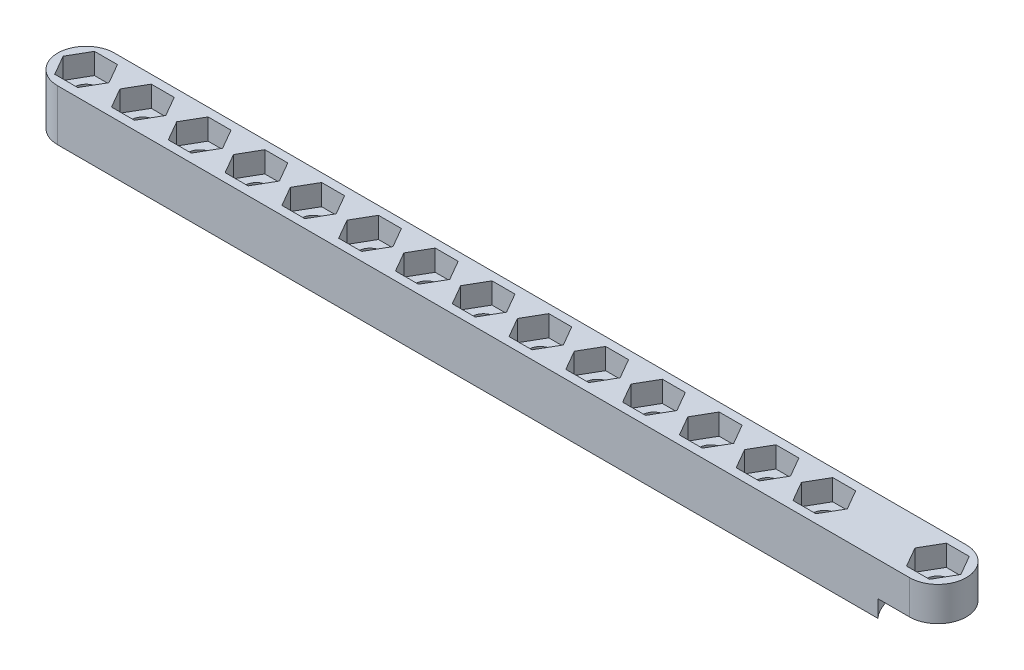
SolidWorks part; units mm, degrees
ref_plane "Front Plane" through (0, 0, 0) normal (0, 0, 1) x (1, 0, 0)
ref_plane "Top Plane" through (0, 0, 0) normal (0, 1, 0) x (1, 0, 0)
ref_plane "Right Plane" through (0, 0, 0) normal (1, 0, 0) x (0, 0, -1)
sketch "Sketch1" plane through (0, 0, 0) normal (0, 1, 0) x (1, 0, 0)
  line L0 (0, 0) -> (-150, 0) construction
  line L1 (0, -5) -> (-150, -5)
  line L2 (0, 5) -> (-150, 5)
  arc A0 (0, -5) -> (0, 5) centre (0, 0) ccw
  arc A1 (-150, 5) -> (-150, -5) centre (-150, 0) ccw
  circle A2 centre (0, 0) radius 2.05
  circle A7 centre (-50, 0) radius 2.05
  circle A8 centre (-60, 0) radius 2.05
  circle A9 centre (-70, 0) radius 2.05
  circle A10 centre (-80, 0) radius 2.05
  circle A11 centre (-90, 0) radius 2.05
  circle A12 centre (-100, 0) radius 2.05
  circle A13 centre (-110, 0) radius 2.05
  circle A14 centre (-120, 0) radius 2.05
  circle A15 centre (-130, 0) radius 2.05
  circle A16 centre (-140, 0) radius 2.05
  circle A17 centre (-150, 0) radius 2.05
  circle A18 centre (-10, 0) radius 2.05 [skipped]
  circle A19 centre (-20, 0) radius 2.05
  circle A20 centre (-30, 0) radius 2.05
  circle A21 centre (-40, 0) radius 2.05
  point P3 (-75, 0)
  dimension "D3" = 4.1
  dimension "D1" = 150
  dimension "D2" = 10
  dimension "D4" = 16
extrude "Boss-Extrude1" add sketch "Sketch1" along normal blind 6
sketch "Sketch2" plane through (0, 6, 0) normal (0, 1, 0) x (1, 0, 0)
  line L1 (4.0415, 0) -> (2.0207, 3.5)
  line L2 (2.0207, 3.5) -> (-2.0207, 3.5)
  line L3 (-2.0207, 3.5) -> (-4.0415, 0)
  line L4 (-4.0415, 0) -> (-2.0207, -3.5)
  line L5 (-2.0207, -3.5) -> (2.0207, -3.5)
  line L6 (2.0207, -3.5) -> (4.0415, 0)
  line L30 (-45.9585, 0) -> (-47.9793, 3.5)
  line L31 (-47.9793, 3.5) -> (-52.0207, 3.5)
  line L32 (-52.0207, 3.5) -> (-54.0415, 0)
  line L33 (-54.0415, 0) -> (-52.0207, -3.5)
  line L34 (-52.0207, -3.5) -> (-47.9793, -3.5)
  line L35 (-47.9793, -3.5) -> (-45.9585, 0)
  line L36 (-55.9585, 0) -> (-57.9793, 3.5)
  line L37 (-57.9793, 3.5) -> (-62.0207, 3.5)
  line L38 (-62.0207, 3.5) -> (-64.0415, 0)
  line L39 (-64.0415, 0) -> (-62.0207, -3.5)
  line L40 (-62.0207, -3.5) -> (-57.9793, -3.5)
  line L41 (-57.9793, -3.5) -> (-55.9585, 0)
  line L42 (-65.9585, 0) -> (-67.9793, 3.5)
  line L43 (-67.9793, 3.5) -> (-72.0207, 3.5)
  line L44 (-72.0207, 3.5) -> (-74.0415, 0)
  line L45 (-74.0415, 0) -> (-72.0207, -3.5)
  line L46 (-72.0207, -3.5) -> (-67.9793, -3.5)
  line L47 (-67.9793, -3.5) -> (-65.9585, 0)
  line L48 (-75.9585, 0) -> (-77.9793, 3.5)
  line L49 (-77.9793, 3.5) -> (-82.0207, 3.5)
  line L50 (-82.0207, 3.5) -> (-84.0415, 0)
  line L51 (-84.0415, 0) -> (-82.0207, -3.5)
  line L52 (-82.0207, -3.5) -> (-77.9793, -3.5)
  line L53 (-77.9793, -3.5) -> (-75.9585, 0)
  line L54 (-85.9585, 0) -> (-87.9793, 3.5)
  line L55 (-87.9793, 3.5) -> (-92.0207, 3.5)
  line L56 (-92.0207, 3.5) -> (-94.0415, 0)
  line L57 (-94.0415, 0) -> (-92.0207, -3.5)
  line L58 (-92.0207, -3.5) -> (-87.9793, -3.5)
  line L59 (-87.9793, -3.5) -> (-85.9585, 0)
  line L60 (-95.9585, 0) -> (-97.9793, 3.5)
  line L61 (-97.9793, 3.5) -> (-102.0207, 3.5)
  line L62 (-102.0207, 3.5) -> (-104.0415, 0)
  line L63 (-104.0415, 0) -> (-102.0207, -3.5)
  line L64 (-102.0207, -3.5) -> (-97.9793, -3.5)
  line L65 (-97.9793, -3.5) -> (-95.9585, 0)
  line L66 (-105.9585, 0) -> (-107.9793, 3.5)
  line L67 (-107.9793, 3.5) -> (-112.0207, 3.5)
  line L68 (-112.0207, 3.5) -> (-114.0415, 0)
  line L69 (-114.0415, 0) -> (-112.0207, -3.5)
  line L70 (-112.0207, -3.5) -> (-107.9793, -3.5)
  line L71 (-107.9793, -3.5) -> (-105.9585, 0)
  line L72 (-115.9585, 0) -> (-117.9793, 3.5)
  line L73 (-117.9793, 3.5) -> (-122.0207, 3.5)
  line L74 (-122.0207, 3.5) -> (-124.0415, 0)
  line L75 (-124.0415, 0) -> (-122.0207, -3.5)
  line L76 (-122.0207, -3.5) -> (-117.9793, -3.5)
  line L77 (-117.9793, -3.5) -> (-115.9585, 0)
  line L78 (-125.9585, 0) -> (-127.9793, 3.5)
  line L79 (-127.9793, 3.5) -> (-132.0207, 3.5)
  line L80 (-132.0207, 3.5) -> (-134.0415, 0)
  line L81 (-134.0415, 0) -> (-132.0207, -3.5)
  line L82 (-132.0207, -3.5) -> (-127.9793, -3.5)
  line L83 (-127.9793, -3.5) -> (-125.9585, 0)
  line L84 (-135.9585, 0) -> (-137.9793, 3.5)
  line L85 (-137.9793, 3.5) -> (-142.0207, 3.5)
  line L86 (-142.0207, 3.5) -> (-144.0415, 0)
  line L87 (-144.0415, 0) -> (-142.0207, -3.5)
  line L88 (-142.0207, -3.5) -> (-137.9793, -3.5)
  line L89 (-137.9793, -3.5) -> (-135.9585, 0)
  line L90 (-145.9585, 0) -> (-147.9793, 3.5)
  line L91 (-147.9793, 3.5) -> (-152.0207, 3.5)
  line L92 (-152.0207, 3.5) -> (-154.0415, 0)
  line L93 (-154.0415, 0) -> (-152.0207, -3.5)
  line L94 (-152.0207, -3.5) -> (-147.9793, -3.5)
  line L95 (-147.9793, -3.5) -> (-145.9585, 0)
  line L96 (-5.9585, 0) -> (-7.9793, 3.5) [skipped]
  line L97 (-7.9793, 3.5) -> (-12.0207, 3.5) [skipped]
  line L98 (-12.0207, 3.5) -> (-14.0415, 0) [skipped]
  line L99 (-14.0415, 0) -> (-12.0207, -3.5) [skipped]
  line L100 (-12.0207, -3.5) -> (-7.9793, -3.5) [skipped]
  line L101 (-7.9793, -3.5) -> (-5.9585, 0) [skipped]
  line L102 (-15.9585, 0) -> (-17.9793, 3.5) [skipped]
  line L103 (-17.9793, 3.5) -> (-22.0207, 3.5) [skipped]
  line L104 (-22.0207, 3.5) -> (-24.0415, 0) [skipped]
  line L105 (-24.0415, 0) -> (-22.0207, -3.5) [skipped]
  line L106 (-22.0207, -3.5) -> (-17.9793, -3.5) [skipped]
  line L107 (-17.9793, -3.5) -> (-15.9585, 0) [skipped]
  line L108 (-25.9585, 0) -> (-27.9793, 3.5) [skipped]
  line L109 (-27.9793, 3.5) -> (-32.0207, 3.5) [skipped]
  line L110 (-32.0207, 3.5) -> (-34.0415, 0) [skipped]
  line L111 (-34.0415, 0) -> (-32.0207, -3.5) [skipped]
  line L112 (-32.0207, -3.5) -> (-27.9793, -3.5) [skipped]
  line L113 (-27.9793, -3.5) -> (-25.9585, 0) [skipped]
  line L114 (-35.9585, 0) -> (-37.9793, 3.5) [skipped]
  line L115 (-37.9793, 3.5) -> (-42.0207, 3.5) [skipped]
  line L116 (-42.0207, 3.5) -> (-44.0415, 0) [skipped]
  line L117 (-44.0415, 0) -> (-42.0207, -3.5) [skipped]
  line L118 (-42.0207, -3.5) -> (-37.9793, -3.5) [skipped]
  line L119 (-37.9793, -3.5) -> (-35.9585, 0) [skipped]
  line L120 (-5.9585, 0) -> (-7.9793, 3.5) [skipped]
  line L121 (-7.9793, 3.5) -> (-12.0207, 3.5) [skipped]
  line L122 (-12.0207, 3.5) -> (-14.0415, 0) [skipped]
  line L123 (-14.0415, 0) -> (-12.0207, -3.5) [skipped]
  line L124 (-12.0207, -3.5) -> (-7.9793, -3.5) [skipped]
  line L125 (-7.9793, -3.5) -> (-5.9585, 0) [skipped]
  line L126 (-15.9585, 0) -> (-17.9793, 3.5)
  line L127 (-17.9793, 3.5) -> (-22.0207, 3.5)
  line L128 (-22.0207, 3.5) -> (-24.0415, 0)
  line L129 (-24.0415, 0) -> (-22.0207, -3.5)
  line L130 (-22.0207, -3.5) -> (-17.9793, -3.5)
  line L131 (-17.9793, -3.5) -> (-15.9585, 0)
  line L132 (-25.9585, 0) -> (-27.9793, 3.5)
  line L133 (-27.9793, 3.5) -> (-32.0207, 3.5)
  line L134 (-32.0207, 3.5) -> (-34.0415, 0)
  line L135 (-34.0415, 0) -> (-32.0207, -3.5)
  line L136 (-32.0207, -3.5) -> (-27.9793, -3.5)
  line L137 (-27.9793, -3.5) -> (-25.9585, 0)
  line L138 (-35.9585, 0) -> (-37.9793, 3.5)
  line L139 (-37.9793, 3.5) -> (-42.0207, 3.5)
  line L140 (-42.0207, 3.5) -> (-44.0415, 0)
  line L141 (-44.0415, 0) -> (-42.0207, -3.5)
  line L142 (-42.0207, -3.5) -> (-37.9793, -3.5)
  line L143 (-37.9793, -3.5) -> (-35.9585, 0)
  circle A0 centre (0, 0) radius 3.5 construction
  circle A5 centre (-50, 0) radius 3.5 construction
  circle A6 centre (-60, 0) radius 3.5 construction
  circle A7 centre (-70, 0) radius 3.5 construction
  circle A8 centre (-80, 0) radius 3.5 construction
  circle A9 centre (-90, 0) radius 3.5 construction
  circle A10 centre (-100, 0) radius 3.5 construction
  circle A11 centre (-110, 0) radius 3.5 construction
  circle A12 centre (-120, 0) radius 3.5 construction
  circle A13 centre (-130, 0) radius 3.5 construction
  circle A14 centre (-140, 0) radius 3.5 construction
  circle A15 centre (-150, 0) radius 3.5 construction
  circle A16 centre (-10, 0) radius 3.5 construction
  circle A17 centre (-20, 0) radius 3.5 construction
  circle A18 centre (-30, 0) radius 3.5 construction
  circle A19 centre (-40, 0) radius 3.5 construction
  dimension "D1" = 7
  dimension "D2" = 16
  dimension "D3" = 5
extrude "Cut-Extrude1" cut sketch "Sketch2" against normal blind 3.7
sketch "Sketch4" plane through (0, 0, 0) normal (0, -1, 0) x (1, 0, 0)
  line L0 (-150, 5) -> (-5.5777, 5)
  line L1 (-150, 5) -> (0, 5) construction
  line L2 (-150, -5) -> (-5.5777, -5)
  line L3 (0, -5) -> (-150, -5) construction
  arc A0 (-150, 5) -> (-150, -5) centre (-150, 0) ccw
  arc A1 (-5.5777, 5) -> (-5.5777, -5) centre (0, 0) ccw
  point P14 (0, 0)
  point P15 (-3.8989, -5)
extrude "Boss-Extrude2" add sketch "Sketch4" along normal blind 3
sketch "Sketch5" plane through (0, -3, 0) normal (0, -1, 0) x (1, 0, 0)
  line L0 (0, 0) -> (-150, 0) construction
  circle A0 centre (-50, 0) radius 2.05
  circle A1 centre (-60, 0) radius 2.05
  circle A2 centre (-70, 0) radius 2.05
  circle A3 centre (-80, 0) radius 2.05
  circle A4 centre (-90, 0) radius 2.05
  circle A5 centre (-100, 0) radius 2.05
  circle A6 centre (-110, 0) radius 2.05
  circle A7 centre (-120, 0) radius 2.05
  circle A8 centre (-130, 0) radius 2.05
  circle A9 centre (-140, 0) radius 2.05
  circle A10 centre (-150, 0) radius 2.05
  circle A11 centre (-40, 0) radius 2.05
  circle A12 centre (-30, 0) radius 2.05
  circle A13 centre (-20, 0) radius 2.05
  dimension "D1" = 11
extrude "Cut-Extrude2" cut sketch "Sketch5" against normal through all
